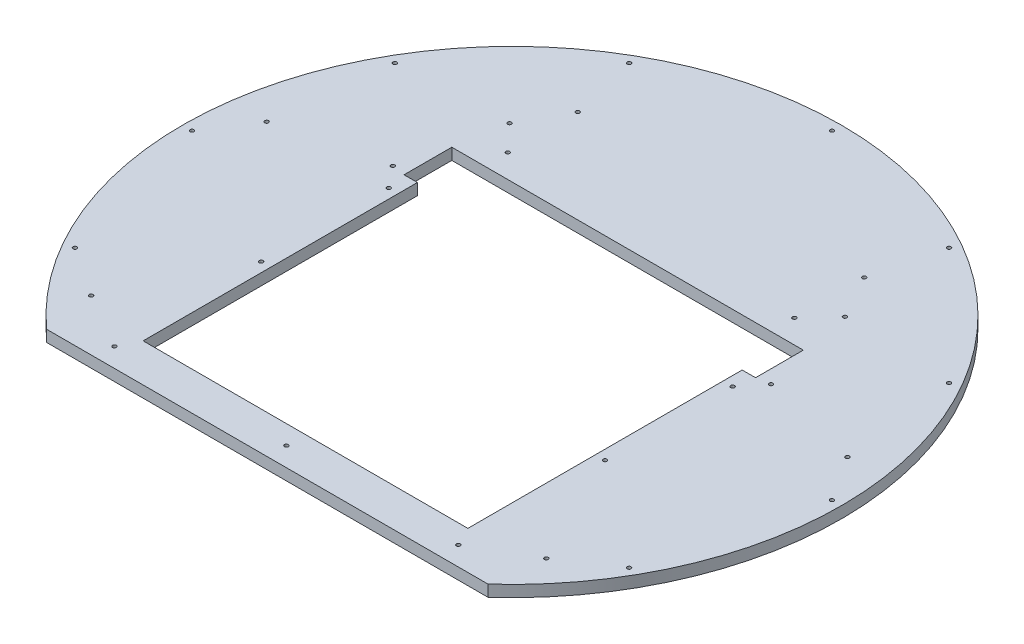
SolidWorks part; units mm, degrees
ref_plane "Front Plane" through (0, 0, 0) normal (0, 0, 1) x (1, 0, 0)
ref_plane "Top Plane" through (0, 0, 0) normal (0, 1, 0) x (1, 0, 0)
ref_plane "Right Plane" through (0, 0, 0) normal (1, 0, 0) x (0, 0, -1)
sketch "Sketch1" plane through (0, 0, 0) normal (0, 1, 0) x (1, 0, 0)
  line L0 (0, 0) -> (0, -162.5) construction
  line L2 (-100, -144.5) -> (100, -144.5)
  line L3 (-100, -144.5) -> (-100, 35.5)
  line L4 (-100, 35.5) -> (100, 35.5)
  line L5 (100, -144.5) -> (100, 35.5)
  line L6 (-100, -144.5) -> (100, 35.5) construction
  line L7 (-100, 35.5) -> (100, -144.5) construction
  circle A0 centre (0, 0) radius 162.5
  point P4 (0, -54.5)
  dimension "D1" = 325
  dimension "D2" = 180
  dimension "D3" = 35.5
  dimension "D4" = 200
sketch "Sketch2" plane through (0, 0, 0) normal (0, 1, 0) x (1, 0, 0)
  line L0 (-100, -144.5) -> (-100, 35.5) construction
  line L1 (-100, 35.5) -> (100, 35.5) construction
  line L2 (100, -144.5) -> (100, 35.5) construction
  line L3 (-100, -128.0869) -> (-100, 35.5)
  line L4 (-100, 35.5) -> (100, 35.5)
  line L5 (100, -128.0869) -> (100, 35.5)
  circle A0 centre (0, 0) radius 162.5 construction
  arc A1 (100, -128.0869) -> (-100, -128.0869) centre (0, 0) ccw
extrude "Boss-Extrude1" add sketch "Sketch2" along normal blind 6
sketch "Sketch4" plane through (0, 6, 0) normal (0, 1, 0) x (1, 0, 0)
  line L0 (0, 0) -> (0, 162.5) construction
  line L1 (119.15, -101.1581) -> (123.8764, -105.1708) construction
  line L2 (100, 35.5) -> (100, -128.0869) construction
  line L4 (-100, 35.5) -> (100, 35.5) construction
  arc A0 (100, -128.0869) -> (-100, -128.0869) centre (0, 0) ccw construction
  circle A1 centre (119.15, -101.1581) radius 1
  circle A2 centre (87.75, 86.5) radius 1
  circle A3 centre (152, 23.5891) radius 1
  circle A4 centre (-87.75, 86.5) radius 1
  circle A5 centre (99, 36.6) radius 1
  circle A6 centre (-99, 36.6) radius 1
  circle A7 centre (-152, 23.5891) radius 1
  circle A8 centre (-119.15, -101.1581) radius 1
  dimension "D1" = 2
  dimension "D3" = 6.2
  dimension "D2" = 129
  dimension "D4" = 19.15
  dimension "D5" = 52
  dimension "D6" = 51
  dimension "D7" = 87.75
  dimension "D8" = 1.1
extrude "Cut-Extrude2" cut sketch "Sketch4" against normal through all
sketch "Sketch5" plane through (0, 6, 0) normal (0, 1, 0) x (1, 0, 0)
  line L0 (-100, -128.0869) -> (-100, 35.5) construction
  line L1 (-100, -108.0869) -> (100, -108.0869)
  line L2 (-100, -108.0869) -> (-100, -128.0869)
  line L3 (-100, -128.0869) -> (100, -128.0869)
  line L4 (100, -108.0869) -> (100, -128.0869)
  dimension "D1" = 20
extrude "Boss-Extrude2" add sketch "Sketch5" against normal blind 6
sketch "Sketch6" plane through (0, 6, 0) normal (0, 1, 0) x (1, 0, 0)
  line L0 (0, 0) -> (0, 162.5) construction
  line L1 (-100, 35.5) -> (100, 35.5) construction
  line L2 (-92, 60.5) -> (92, 60.5)
  line L3 (-92, 60.5) -> (-92, 35.5)
  line L4 (-92, 35.5) -> (92, 35.5)
  line L5 (92, 60.5) -> (92, 35.5)
  line L6 (-92, 60.5) -> (92, 35.5) construction
  line L7 (-92, 35.5) -> (92, 60.5) construction
  line L8 (100, 35.5) -> (100, -108.0869) construction
  arc A0 (100, -128.0869) -> (-100, -128.0869) centre (0, 0) ccw construction
  point P6 (0, 48)
  dimension "D1" = 8
  dimension "D2" = 25
extrude "Cut-Extrude3" cut sketch "Sketch6" against normal through all
sketch "Sketch7" plane through (0, 6, 0) normal (0, 1, 0) x (1, 0, 0)
  line L0 (0, 0) -> (0, 162.5) construction
  line L1 (92, 60.5) -> (-92, 60.5) construction
  circle A0 centre (-75, 72.8) radius 1
  circle A1 centre (-75, 109.4) radius 1
  arc A2 (100, -128.0869) -> (-100, -128.0869) centre (0, 0) ccw construction
  circle A3 centre (75, 109.4) radius 1
  circle A4 centre (75, 72.8) radius 1
  dimension "D4" = 2
  dimension "D1" = 36.6
  dimension "D2" = 150
  dimension "D3" = 12.3
extrude "Cut-Extrude4" cut sketch "Sketch7" against normal blind 6
sketch "Sketch8" plane through (0, 6, 0) normal (0, 1, 0) x (1, 0, 0)
  line L0 (-100, -128.0869) -> (-115.5422, -128.0869)
  line L1 (100, -128.0869) -> (115.5422, -128.0869)
  arc A0 (115.5422, -128.0869) -> (-115.5422, -128.0869) centre (0, 0) ccw
  arc A1 (100, -128.0869) -> (-100, -128.0869) centre (0, 0) ccw construction
  arc A2 (100, -128.0869) -> (-100, -128.0869) centre (0, 0) ccw
  dimension "D1" = 10
extrude "Boss-Extrude3" add sketch "Sketch8" against normal through all
sketch "Sketch9" plane through (0, 6, 0) normal (0, 1, 0) x (1, 0, 0)
  line L0 (0, 172.5) -> (0, 162.5) construction
  arc A0 (115.5422, -128.0869) -> (-115.5422, -128.0869) centre (0, 0) ccw construction
  circle A1 centre (0, 0) radius 162.5 construction
  circle A2 centre (0, 167.5) radius 1
  circle A3 centre (83.75, 145.0593) radius 1
  circle A4 centre (145.0593, 83.75) radius 1
  circle A5 centre (167.5, 0) radius 1
  circle A6 centre (145.0593, -83.75) radius 1
  circle A7 centre (83.75, -145.0593) radius 1
  circle A8 centre (0, -167.5) radius 1
  circle A9 centre (-83.75, -145.0593) radius 1
  circle A10 centre (-145.0593, -83.75) radius 1
  circle A11 centre (-167.5, 0) radius 1
  circle A12 centre (-145.0593, 83.75) radius 1
  circle A13 centre (-83.75, 145.0593) radius 1
  point P36 (0, 0)
  dimension "D1" = 2
  dimension "D2" = 12
extrude "Cut-Extrude5" cut sketch "Sketch9" against normal through all
sketch "Sketch10" plane through (0, 6, 0) normal (0, 1, 0) x (1, 0, 0)
  line L0 (-100, 35.5) -> (100, 35.5) construction
  line L1 (-100, -108.0869) -> (-85, -108.0869)
  line L2 (-100, -108.0869) -> (-100, 35.5)
  line L3 (-100, 35.5) -> (-85, 35.5)
  line L4 (-85, -108.0869) -> (-85, 35.5)
  line L5 (0, 0) -> (0, 60.5) construction
  line L6 (92, 60.5) -> (-92, 60.5) construction
  line L7 (85, -108.0869) -> (85, 35.5)
  line L8 (100, 35.5) -> (85, 35.5)
  line L9 (100, -108.0869) -> (100, 35.5)
  line L10 (100, -108.0869) -> (85, -108.0869)
  dimension "D1" = 15
extrude "Boss-Extrude4" add sketch "Sketch10" against normal through all
sketch "Sketch11" plane through (0, 6, 0) normal (0, 1, 0) x (1, 0, 0)
  line L0 (-125.7447, -118.0869) -> (125.7447, -118.0869) construction
  line L1 (-115.5422, -128.0869) -> (115.5422, -128.0869) construction
  line L2 (-90, -118.0869) -> (-90, 35.5) construction
  line L3 (-100, 35.5) -> (100, 35.5) construction
  line L4 (-100, -144.5) -> (-100, 35.5) construction
  line L5 (90, 35.5) -> (90, -118.0869) construction
  line L6 (100, -144.5) -> (100, 35.5) construction
  line L7 (0, 0) -> (0, 60.5) construction
  line L8 (92, 60.5) -> (-92, 60.5) construction
  arc A0 (115.5422, -128.0869) -> (-115.5422, -128.0869) centre (0, 0) ccw construction
  circle A1 centre (-90, -118.0869) radius 1
  circle A2 centre (0, -118.0869) radius 1
  circle A3 centre (90, -118.0869) radius 1
  circle A4 centre (-90, 25.5) radius 1
  circle A5 centre (-90, -41.2934) radius 1
  circle A6 centre (90, -41.2934) radius 1
  circle A7 centre (90, 25.5) radius 1
  dimension "D5" = 2
  dimension "D1" = 10
  dimension "D2" = 10
  dimension "D3" = 10
  dimension "D4" = 10
extrude "Cut-Extrude6" cut sketch "Sketch11" against normal through all
